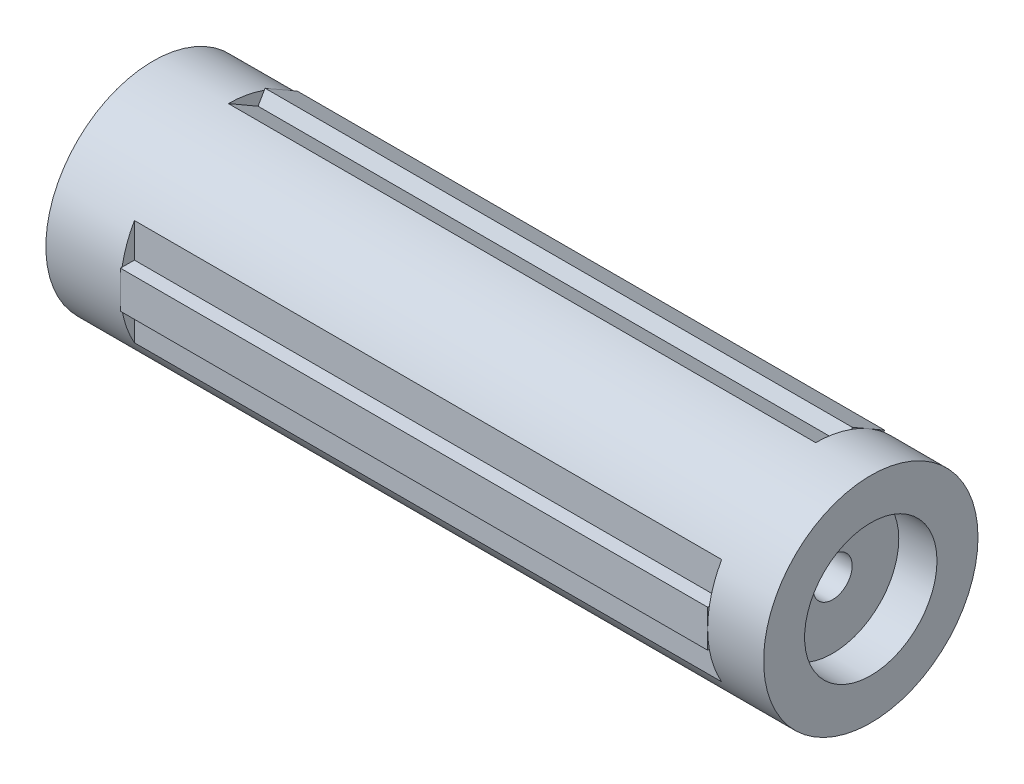
SolidWorks part; units mm, degrees
material "PVC hart"
ref_plane "Ebene vorne" through (0, 0, 0) normal (0, 0, 1) x (1, 0, 0)
ref_plane "Ebene oben" through (0, 0, 0) normal (0, 1, 0) x (1, 0, 0)
ref_plane "Ebene rechts" through (0, 0, 0) normal (1, 0, 0) x (0, 0, -1)
sketch "Skizze1" plane through (0, 0, 0) normal (1, 0, 0) x (0, 0, -1)
  circle A0 centre (0, 0) radius 11.5
  dimension "D1" = 23
extrude "Aufsatz-Linear austragen1" add sketch "Skizze1" along normal blind 77
sketch "Skizze2" plane through (77, 0, 0) normal (1, 0, 0) x (0, 0, -1)
  circle A0 centre (0, 0) radius 7.1
  dimension "D1" = 14.2
extrude "Schnitt-Linear austragen1" cut sketch "Skizze2" against normal blind 4.1
sketch "Skizze3" plane through (72.9, 0, 0) normal (1, 0, 0) x (0, 0, -1)
  circle A0 centre (0, 0) radius 2.1
  dimension "D1" = 4.2
extrude "Schnitt-Linear austragen2" cut sketch "Skizze3" against normal blind 3
sketch "Skizze4" plane through (0, 0, 0) normal (-1, 0, 0) x (0, 0, 1)
  circle A0 centre (0, 0) radius 9.6
  dimension "D1" = 19.2
extrude "Schnitt-Linear austragen3" cut sketch "Skizze4" against normal blind 12.75
sketch "Skizze7" plane through (77, 0, 0) normal (1, 0, 0) x (0, 0, -1)
  line L0 (0, 13.4409) -> (0, -14.2481) construction
  line L1 (-11.5, 7.5) -> (-10, 7.5)
  line L2 (-11.5, 7.5) -> (-11.5, -7.5)
  line L3 (-11.5, -7.5) -> (-10, -7.5)
  line L4 (-10, 7.5) -> (-10, -7.5)
  dimension "D1" = 1.5
  dimension "D2" = 15
  dimension "D3" = 10
extrude "Schnitt-Linear austragen4" cut sketch "Skizze7" against normal blind 63 from offset 6 offset against normal yes
sketch "Skizze8" plane through (0, 0, 10) normal (0, 0, 1) x (1, 0, 0)
  line L0 (71, -5.6789) -> (71, 5.6789) construction
  line L1 (8, 2) -> (71, 2)
  line L2 (8, 2) -> (8, -2)
  line L3 (8, -2) -> (71, -2)
  line L4 (71, 2) -> (71, -2)
  line L5 (8, 2) -> (71, -2) construction
  line L6 (8, -2) -> (71, 2) construction
  line L7 (12.65, 0) -> (-12.65, 0) construction
  point P0 (39.5, 0)
  dimension "D1" = 31.5
  dimension "D3" = 63
  dimension "D4" = 4
extrude "Aufsatz-Linear austragen2" add sketch "Skizze8" along normal blind 1.5
sketch "Skizze10" plane through (12.75, 0, 0) normal (-1, 0, 0) x (0, 0, 1)
  line L1 (4.0389, -2.2407) -> (3.96, 2.3774)
  line L2 (3.96, 2.3774) -> (-0.0789, 4.6181)
  line L3 (-0.0789, 4.6181) -> (-4.0389, 2.2407)
  line L4 (-4.0389, 2.2407) -> (-3.96, -2.3774)
  line L5 (-3.96, -2.3774) -> (0.0789, -4.6181)
  line L6 (0.0789, -4.6181) -> (4.0389, -2.2407)
  circle A0 centre (0, 0) radius 4 construction
  dimension "D1" = 8
extrude "Schnitt-Linear austragen6" cut sketch "Skizze10" against normal blind 13.5
sketch "Skizze12" plane through (26.25, 0, 0) normal (-1, 0, 0) x (0, 0, 1)
  circle A0 centre (0, 0) radius 3
  dimension "D1" = 6
extrude "Schnitt-Linear austragen7" cut sketch "Skizze12" against normal blind 2
pattern_circular "Kreismuster3" count 3 over 360 about axis through (0, 0, 0) along (1, 0, 0) of "Aufsatz-Linear austragen2", "Schnitt-Linear austragen4"
sketch "Skizze13" plane through (69.9, 0, 0) normal (1, 0, 0) x (0, 0, -1)
  circle A0 centre (0, 0) radius 8.5
extrude "Schnitt-Linear austragen8" cut sketch "Skizze13" against normal blind 40
